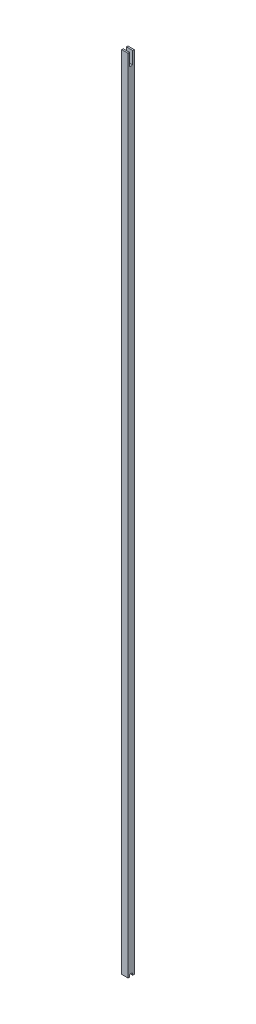
SolidWorks part; units mm, degrees
ref_plane "Front Plane" through (0, 0, 0) normal (0, 0, 1) x (1, 0, 0)
ref_plane "Top Plane" through (0, 0, 0) normal (0, 1, 0) x (1, 0, 0)
ref_plane "Right Plane" through (0, 0, 0) normal (1, 0, 0) x (0, 0, -1)
sketch "Sketch1" plane through (0, 0, 0) normal (1, 0, 0) x (0, 0, -1)
  line L0 (0, 0) -> (1.5875, 0)
  line L1 (1.5875, 0) -> (1.5875, 2.3813)
  line L2 (1.5875, 2.3813) -> (4.7625, 2.3813)
  line L3 (4.7625, 2.3813) -> (4.7625, 0)
  line L4 (4.7625, 0) -> (6.35, 0)
  line L5 (6.35, 0) -> (6.35, 812.8)
  line L6 (6.35, 812.8) -> (4.7625, 812.8)
  line L7 (4.7625, 812.8) -> (4.7625, 800.1)
  line L8 (4.7625, 800.1) -> (1.5875, 800.1)
  line L9 (1.5875, 800.1) -> (1.5875, 812.8)
  line L10 (1.5875, 812.8) -> (0, 812.8)
  line L11 (0, 812.8) -> (0, 0)
extrude "Boss-Extrude1" add sketch "Sketch1" along normal blind 6.35
